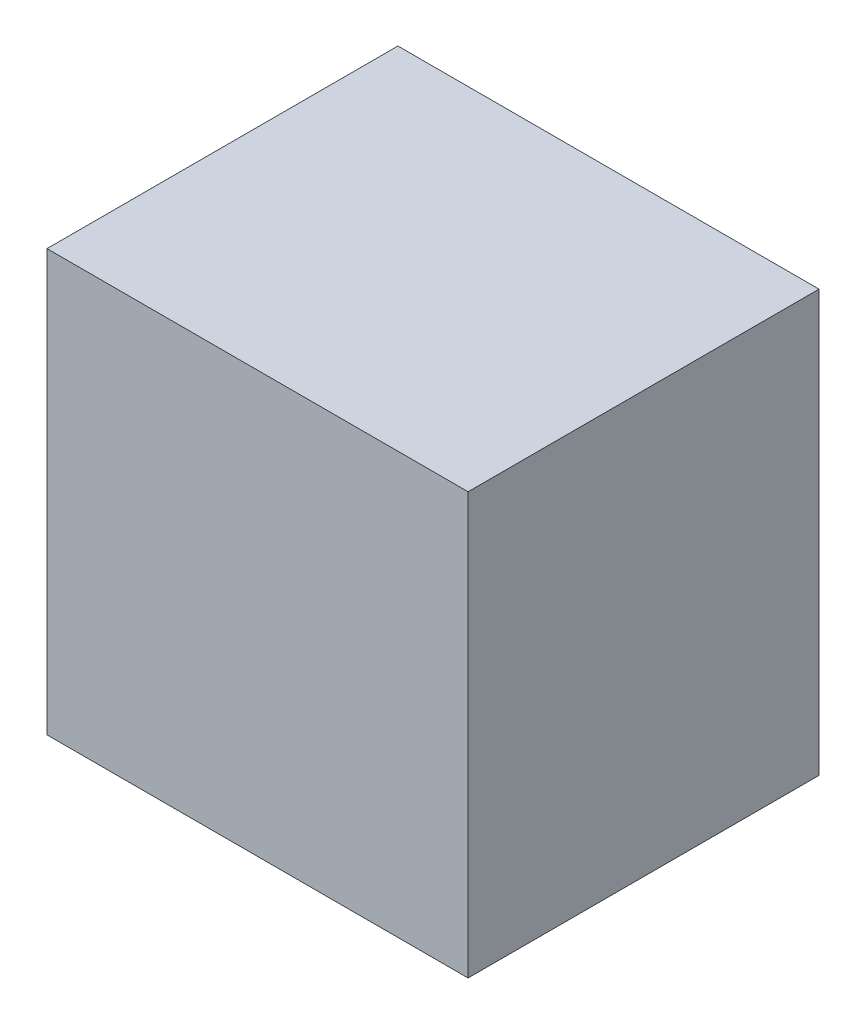
SolidWorks part; units mm, degrees
ref_plane "前视基准面" through (0, 0, 0) normal (0, 0, 1) x (1, 0, 0)
ref_plane "上视基准面" through (0, 0, 0) normal (0, 1, 0) x (1, 0, 0)
ref_plane "右视基准面" through (0, 0, 0) normal (1, 0, 0) x (0, 0, -1)
other "Configuration Table"
sketch "草图1" plane through (0, 0, 0) normal (0, 0, 1) x (1, 0, 0)
  line L1 (-30, -30) -> (30, -30)
  line L2 (-30, -30) -> (-30, 30)
  line L3 (-30, 30) -> (30, 30)
  line L4 (30, -30) -> (30, 30)
  line L5 (-30, -30) -> (30, 30) construction
  line L6 (-30, 30) -> (30, -30) construction
  point P0 (0, 0)
extrude "凸台-拉伸1" add sketch "草图1" along normal blind 50
